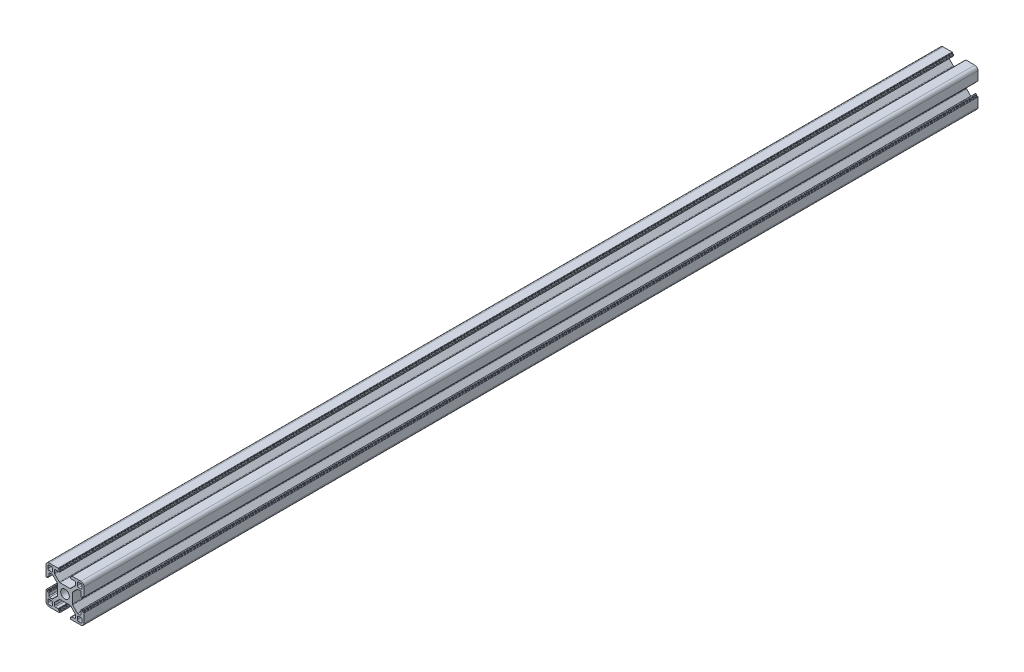
SolidWorks part; units mm, degrees
material "6063-T5"
ref_plane "Front Plane" through (0, 0, 0) normal (0, 0, 1) x (1, 0, 0)
ref_plane "Top Plane" through (0, 0, 0) normal (0, 1, 0) x (1, 0, 0)
ref_plane "Right Plane" through (0, 0, 0) normal (1, 0, 0) x (0, 0, -1)
sketch "Sketch1" plane through (0, 0, 0) normal (0, 0, 1) x (1, 0, 0)
  line L0 (0, 2.5) -> (0, 10.6)
  line L1 (2.5, 30) -> (9.5, 30)
  line L2 (30, 27.5) -> (30, 20.5)
  line L3 (27.5, 0) -> (19.4, 0)
  line L4 (19.464, 9.1128) -> (23.1303, 5.4465)
  line L5 (21.0197, 10.536) -> (24.686, 6.8697)
  line L6 (10.536, 21.0197) -> (6.8697, 24.686)
  line L7 (8.9803, 19.464) -> (5.314, 23.1303)
  line L8 (11.0663, 20.8) -> (18.9337, 20.8)
  line L9 (20.8, 18.9337) -> (20.8, 11.0663)
  line L10 (18.9337, 9.3324) -> (11.0663, 9.3324)
  line L11 (9.2, 11.0663) -> (9.2, 18.9337)
  line L12 (0, 19.4) -> (0, 27.5)
  line L13 (30, 9.5) -> (30, 2.5)
  line L14 (19.4, 27.8) -> (22.6, 27.8)
  line L15 (10.6, 27.8) -> (7.4, 27.8)
  line L16 (10.6, 0) -> (2.5, 0)
  line L17 (2.2, 20.5) -> (2.2, 22.6)
  line L18 (2.2, 9.5) -> (2.2, 7.4)
  line L19 (9.5, 2.3324) -> (7.4, 2.3324)
  line L20 (19.464, 21.0197) -> (23.1303, 24.686)
  line L21 (21.0197, 19.464) -> (24.686, 23.1303)
  line L22 (8.9803, 10.536) -> (5.314, 6.8697)
  line L23 (10.536, 9.1128) -> (6.8697, 5.4465)
  line L24 (10.8, 28.8) -> (10.8, 28)
  line L25 (19.2, 28.8) -> (19.2, 28)
  line L26 (0.2, 19.2) -> (1, 19.2)
  line L27 (0.2, 10.8) -> (1, 10.8)
  line L28 (28.8, 19.2) -> (28, 19.2)
  line L29 (28.8, 10.8) -> (28, 10.8)
  line L30 (10.8, 0.2) -> (10.8, 1.1324)
  line L31 (19.2, 0.2) -> (19.2, 1.1324)
  line L32 (20.5, 30) -> (27.5, 30)
  line L33 (27.8, 19.4) -> (27.8, 22.6)
  line L34 (27.8, 10.6) -> (27.8, 7.4)
  line L35 (20.5, 2.2) -> (22.6, 2.2)
  line L36 (6.65, 27.05) -> (6.65, 25.2163)
  line L37 (23.35, 27.05) -> (23.35, 25.2163)
  line L38 (2.95, 23.35) -> (4.7837, 23.35)
  line L39 (27.05, 23.35) -> (25.2163, 23.35)
  line L40 (2.95, 6.65) -> (4.7837, 6.65)
  line L41 (6.65, 3.0824) -> (6.65, 4.9161)
  line L42 (23.35, 2.95) -> (23.35, 4.9161)
  line L43 (27.05, 6.65) -> (25.2163, 6.65)
  line L44 (29, 10.6) -> (29, 9.9)
  line L45 (29.8, 20.3) -> (29.2, 20.3)
  line L46 (29, 20.1) -> (29, 19.4)
  line L47 (29.2, 9.7) -> (29.8, 9.7)
  line L48 (19.4, 29) -> (20.1, 29)
  line L49 (9.7, 29.8) -> (9.7, 29.2)
  line L50 (9.9, 29) -> (10.6, 29)
  line L51 (20.3, 29.2) -> (20.3, 29.8)
  line L52 (9.7, 2.1324) -> (9.7, 1.5324)
  line L53 (9.9, 1.3324) -> (10.6, 1.3324)
  line L54 (19.4, 1.3324) -> (20.1, 1.3324)
  line L55 (20.3, 1.5324) -> (20.3, 2)
  line L56 (2, 20.3) -> (1.4, 20.3)
  line L57 (1.2, 20.1) -> (1.2, 19.4)
  line L58 (1.2, 10.6) -> (1.2, 9.9)
  line L59 (1.4, 9.7) -> (2, 9.7)
  line L60 (27.55, 1.45) -> (25.8, 1.45)
  line L61 (24.8, 2.45) -> (24.8, 4.2)
  line L62 (25.8, 5.2) -> (27.55, 5.2)
  line L63 (28.55, 4.2) -> (28.55, 2.45)
  line L64 (24.8, 25.8) -> (24.8, 27.55)
  line L65 (25.8, 28.55) -> (27.55, 28.55)
  line L66 (28.55, 27.55) -> (28.55, 25.8)
  line L67 (27.55, 24.8) -> (25.8, 24.8)
  line L68 (2.45, 28.55) -> (4.2, 28.55)
  line L69 (5.2, 27.55) -> (5.2, 25.8)
  line L70 (1.45, 2.45) -> (1.45, 4.2)
  line L71 (2.45, 5.2) -> (4.2, 5.2)
  line L72 (5.2, 4.2) -> (5.2, 2.45)
  line L73 (4.2, 1.45) -> (2.45, 1.45)
  line L74 (4.2, 24.8) -> (2.45, 24.8)
  line L75 (1.45, 25.8) -> (1.45, 27.55)
  circle A0 centre (15, 15) radius 3.4
  arc A1 (25.8, 1.45) -> (24.8, 2.45) centre (25.8, 2.45) cw
  arc A2 (27.55, 1.45) -> (28.55, 2.45) centre (27.55, 2.45) ccw
  arc A3 (27.55, 5.2) -> (28.55, 4.2) centre (27.55, 4.2) cw
  arc A4 (24.8, 4.2) -> (25.8, 5.2) centre (25.8, 4.2) cw
  arc A5 (1.45, 2.45) -> (2.45, 1.45) centre (2.45, 2.45) ccw
  arc A6 (5.2, 2.45) -> (4.2, 1.45) centre (4.2, 2.45) cw
  arc A7 (4.2, 5.2) -> (5.2, 4.2) centre (4.2, 4.2) cw
  arc A8 (1.45, 4.2) -> (2.45, 5.2) centre (2.45, 4.2) cw
  arc A9 (24.8, 25.8) -> (25.8, 24.8) centre (25.8, 25.8) ccw
  arc A10 (28.55, 25.8) -> (27.55, 24.8) centre (27.55, 25.8) cw
  arc A11 (27.55, 28.55) -> (28.55, 27.55) centre (27.55, 27.55) cw
  arc A12 (24.8, 27.55) -> (25.8, 28.55) centre (25.8, 27.55) cw
  arc A13 (4.2, 28.55) -> (5.2, 27.55) centre (4.2, 27.55) cw
  arc A14 (5.2, 25.8) -> (4.2, 24.8) centre (4.2, 25.8) cw
  arc A15 (2.45, 24.8) -> (1.45, 25.8) centre (2.45, 25.8) cw
  arc A16 (2.45, 28.55) -> (1.45, 27.55) centre (2.45, 27.55) ccw
  arc A17 (30, 2.5) -> (27.5, 0) centre (27.5, 2.5) cw
  arc A18 (0, 2.5) -> (2.5, 0) centre (2.5, 2.5) ccw
  arc A19 (27.5, 30) -> (30, 27.5) centre (27.5, 27.5) cw
  arc A20 (0, 27.5) -> (2.5, 30) centre (2.5, 27.5) cw
  arc A21 (0, 10.6) -> (0.2, 10.8) centre (0.2, 10.6) cw
  arc A22 (1.2, 10.6) -> (1, 10.8) centre (1, 10.6) ccw
  arc A23 (2, 9.7) -> (2.2, 9.5) centre (2, 9.5) cw
  arc A24 (9.7, 2.1324) -> (9.5, 2.3324) centre (9.5, 2.1324) ccw
  arc A25 (10.6, 1.3324) -> (10.8, 1.1324) centre (10.6, 1.1324) cw
  arc A26 (10.6, 0) -> (10.8, 0.2) centre (10.6, 0.2) ccw
  arc A27 (19.4, 0) -> (19.2, 0.2) centre (19.4, 0.2) cw
  arc A28 (19.4, 1.3324) -> (19.2, 1.1324) centre (19.4, 1.1324) ccw
  arc A29 (20.3, 2) -> (20.5, 2.2) centre (20.5, 2) cw
  arc A30 (28, 10.8) -> (27.8, 10.6) centre (28, 10.6) ccw
  arc A31 (29, 10.6) -> (28.8, 10.8) centre (28.8, 10.6) ccw
  arc A32 (29.8, 9.7) -> (30, 9.5) centre (29.8, 9.5) cw
  arc A33 (28, 19.2) -> (27.8, 19.4) centre (28, 19.4) cw
  arc A34 (29, 19.4) -> (28.8, 19.2) centre (28.8, 19.4) cw
  arc A35 (30, 20.5) -> (29.8, 20.3) centre (29.8, 20.5) cw
  arc A36 (20.3, 29.8) -> (20.5, 30) centre (20.5, 29.8) cw
  arc A37 (19.4, 29) -> (19.2, 28.8) centre (19.4, 28.8) ccw
  arc A38 (19.2, 28) -> (19.4, 27.8) centre (19.4, 28) ccw
  arc A39 (10.8, 28) -> (10.6, 27.8) centre (10.6, 28) cw
  arc A40 (0, 19.4) -> (0.2, 19.2) centre (0.2, 19.4) ccw
  arc A41 (1.2, 19.4) -> (1, 19.2) centre (1, 19.4) cw
  arc A42 (2, 20.3) -> (2.2, 20.5) centre (2, 20.5) ccw
  arc A43 (10.6, 29) -> (10.8, 28.8) centre (10.6, 28.8) cw
  arc A44 (9.5, 30) -> (9.7, 29.8) centre (9.5, 29.8) cw
  arc A45 (1.4, 20.3) -> (1.2, 20.1) centre (1.4, 20.1) ccw
  arc A46 (20.1, 29) -> (20.3, 29.2) centre (20.1, 29.2) ccw
  arc A47 (9.7, 29.2) -> (9.9, 29) centre (9.9, 29.2) ccw
  arc A48 (29.2, 20.3) -> (29, 20.1) centre (29.2, 20.1) ccw
  arc A49 (29, 9.9) -> (29.2, 9.7) centre (29.2, 9.9) ccw
  arc A50 (20.1, 1.3324) -> (20.3, 1.5324) centre (20.1, 1.5324) ccw
  arc A51 (1.2, 9.9) -> (1.4, 9.7) centre (1.4, 9.9) ccw
  arc A52 (9.7, 1.5324) -> (9.9, 1.3324) centre (9.9, 1.5324) ccw
  arc A53 (23.35, 25.2163) -> (23.1303, 24.686) centre (22.6, 25.2163) cw
  arc A54 (25.2163, 23.35) -> (24.686, 23.1303) centre (25.2163, 22.6) ccw
  arc A55 (20.8, 18.9337) -> (21.0197, 19.464) centre (21.55, 18.9337) cw
  arc A56 (18.9337, 20.8) -> (19.464, 21.0197) centre (18.9337, 21.55) ccw
  arc A57 (6.65, 25.2163) -> (6.8697, 24.686) centre (7.4, 25.2163) ccw
  arc A58 (11.0663, 20.8) -> (10.536, 21.0197) centre (11.0663, 21.55) cw
  arc A59 (4.7837, 23.35) -> (5.314, 23.1303) centre (4.7837, 22.6) cw
  arc A60 (9.2, 18.9337) -> (8.9803, 19.464) centre (8.45, 18.9337) ccw
  arc A61 (4.7837, 6.65) -> (5.314, 6.8697) centre (4.7837, 7.4) ccw
  arc A62 (9.2, 11.0663) -> (8.9803, 10.536) centre (8.45, 11.0663) cw
  arc A63 (6.65, 4.9161) -> (6.8697, 5.4465) centre (7.4, 4.9161) cw
  arc A64 (11.0663, 9.3324) -> (10.536, 9.1128) centre (11.0663, 8.5824) ccw
  arc A65 (18.9337, 9.3324) -> (19.464, 9.1128) centre (18.9337, 8.5824) cw
  arc A66 (20.8, 11.0663) -> (21.0197, 10.536) centre (21.55, 11.0663) ccw
  arc A67 (25.2163, 6.65) -> (24.686, 6.8697) centre (25.2163, 7.4) cw
  arc A68 (23.35, 4.9161) -> (23.1303, 5.4465) centre (22.6, 4.9161) ccw
  arc A69 (7.4, 2.3324) -> (6.65, 3.0824) centre (7.4, 3.0824) cw
  arc A70 (22.6, 2.2) -> (23.35, 2.95) centre (22.6, 2.95) ccw
  arc A71 (27.8, 7.4) -> (27.05, 6.65) centre (27.05, 7.4) cw
  arc A72 (27.8, 22.6) -> (27.05, 23.35) centre (27.05, 22.6) ccw
  arc A73 (22.6, 27.8) -> (23.35, 27.05) centre (22.6, 27.05) cw
  arc A74 (2.2, 7.4) -> (2.95, 6.65) centre (2.95, 7.4) ccw
  arc A75 (2.2, 22.6) -> (2.95, 23.35) centre (2.95, 22.6) cw
  arc A76 (7.4, 27.8) -> (6.65, 27.05) centre (7.4, 27.05) ccw
  point P115 (0, 0)
extrude "Boss-Extrude1" add sketch "Sketch1" along normal blind 706
